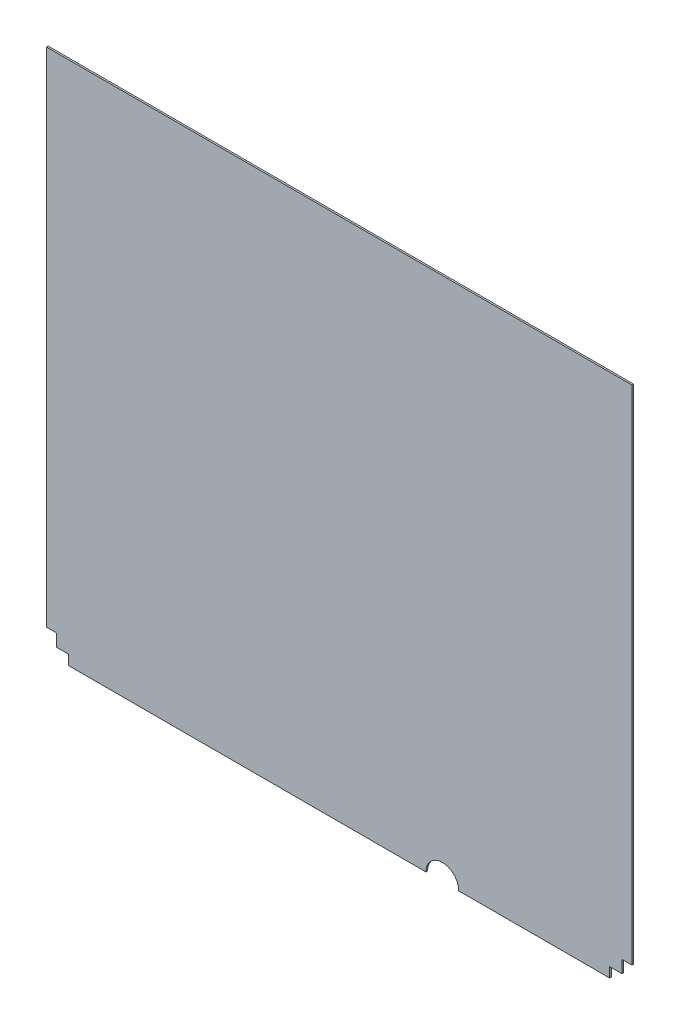
SolidWorks part; units mm, degrees
ref_plane "Front Plane" through (0, 0, 0) normal (0, 0, 1) x (1, 0, 0)
ref_plane "Top Plane" through (0, 0, 0) normal (0, 1, 0) x (1, 0, 0)
ref_plane "Right Plane" through (0, 0, 0) normal (1, 0, 0) x (0, 0, -1)
sketch "Sketch1" plane through (0, 0, 0) normal (0, 0, 1) x (1, 0, 0)
  line L0 (0, 34.544) -> (15.24, 34.544)
  line L1 (0, 0) -> (907.001, 0)
  line L2 (0, 0) -> (0, 812.8)
  line L3 (0, 812.8) -> (907.001, 812.8)
  line L4 (907.001, 0) -> (907.001, 812.8)
  line L5 (0, 0) -> (914.4, 0) construction
  line L6 (0, 0) -> (0, 914.4) construction
  line L7 (0, 914.4) -> (914.4, 914.4) construction
  line L8 (914.4, 0) -> (914.4, 914.4) construction
  line L9 (15.24, 34.544) -> (15.24, 15.24)
  line L10 (15.24, 15.24) -> (34.544, 15.24)
  line L11 (34.544, 15.24) -> (34.544, 0)
  line L12 (907.001, 34.544) -> (891.761, 34.544)
  line L13 (891.761, 34.544) -> (891.761, 15.24)
  line L14 (891.761, 15.24) -> (872.457, 15.24)
  line L15 (872.457, 15.24) -> (872.457, 0)
  arc A0 (638.7043, 0) -> (587.9043, 0) centre (613.3043, 0) ccw
  dimension "D13" = 25.4
  dimension "D1" = 812.8
  dimension "D2" = 907.001
  dimension "D3" = 914.4
  dimension "D4" = 914.4
  dimension "D5" = 15.24
  dimension "D6" = 15.24
  dimension "D7" = 34.544
  dimension "D8" = 34.544
  dimension "D9" = 15.24
  dimension "D10" = 15.24
  dimension "D11" = 34.544
  dimension "D12" = 34.544
extrude "Boss-Extrude1" add sketch "Sketch1" along normal blind 2.54 contours L15 L14 L13 L12 L4 L3 L2 L0 L9 L10 L11 L1
